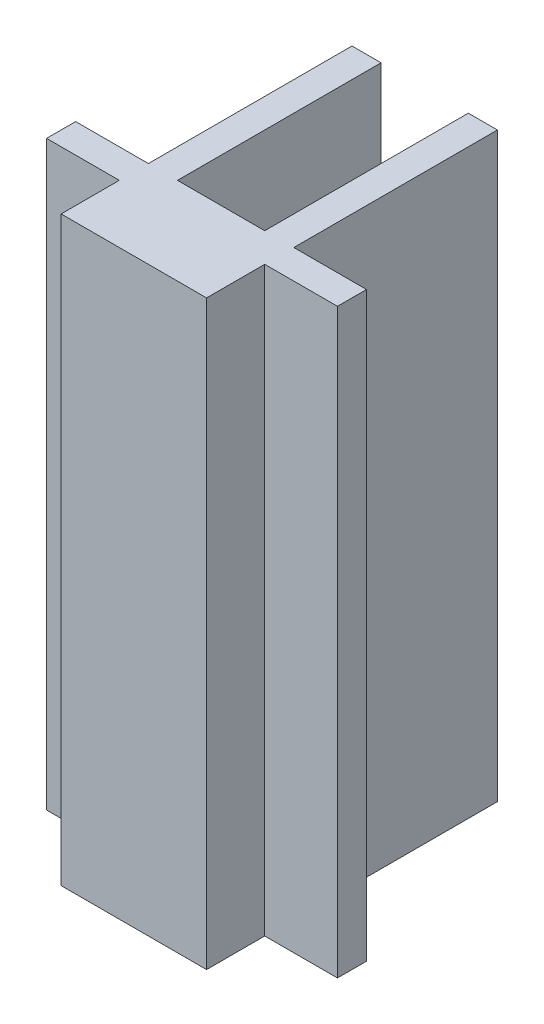
SolidWorks part; units mm, degrees
ref_plane "Спереди" through (0, 0, 0) normal (0, 0, 1) x (1, 0, 0)
ref_plane "Сверху" through (0, 0, 0) normal (0, 1, 0) x (1, 0, 0)
ref_plane "Справа" through (0, 0, 0) normal (1, 0, 0) x (0, 0, -1)
sketch "Эскиз1" plane through (0, 0, 0) normal (0, 1, 0) x (1, 0, 0)
  line L0 (-5, 2) -> (0, 40)
  line L1 (-5, -40) -> (5, -40)
  line L2 (-5, -40) -> (-5, 40)
  line L3 (-5, 40) -> (5, 40)
  line L4 (5, -40) -> (5, 40)
  line L5 (-5, -40) -> (5, 40) construction
  line L6 (-5, 40) -> (5, -40) construction
  line L7 (5, -40) -> (30, -40)
  line L8 (5, -40) -> (5, -30)
  line L9 (5, -30) -> (30, -30)
  line L10 (30, -40) -> (30, -30)
  line L11 (5, -30) -> (-20, -30)
  line L12 (5, -30) -> (5, -60)
  line L13 (5, -60) -> (-20, -60)
  line L14 (-20, -30) -> (-20, -60)
  point P0 (0, 0)
  dimension "D1" = 10
  dimension "D2" = 80
  dimension "D3" = 10
  dimension "D4" = 30
  dimension "D5" = 25
  dimension "D6" = 25
  dimension "D7" = 38
extrude "Бобышка-Вытянуть1" add sketch "Эскиз1" along normal blind 200 contours L11 L4 L3 L0 L2 | L7 L10 L9 L4 | L3 L2 L0
mirror "Зеркальное отражение1" about plane through (-20, 200, 30) normal (1, 0, 0) of "Бобышка-Вытянуть1"
